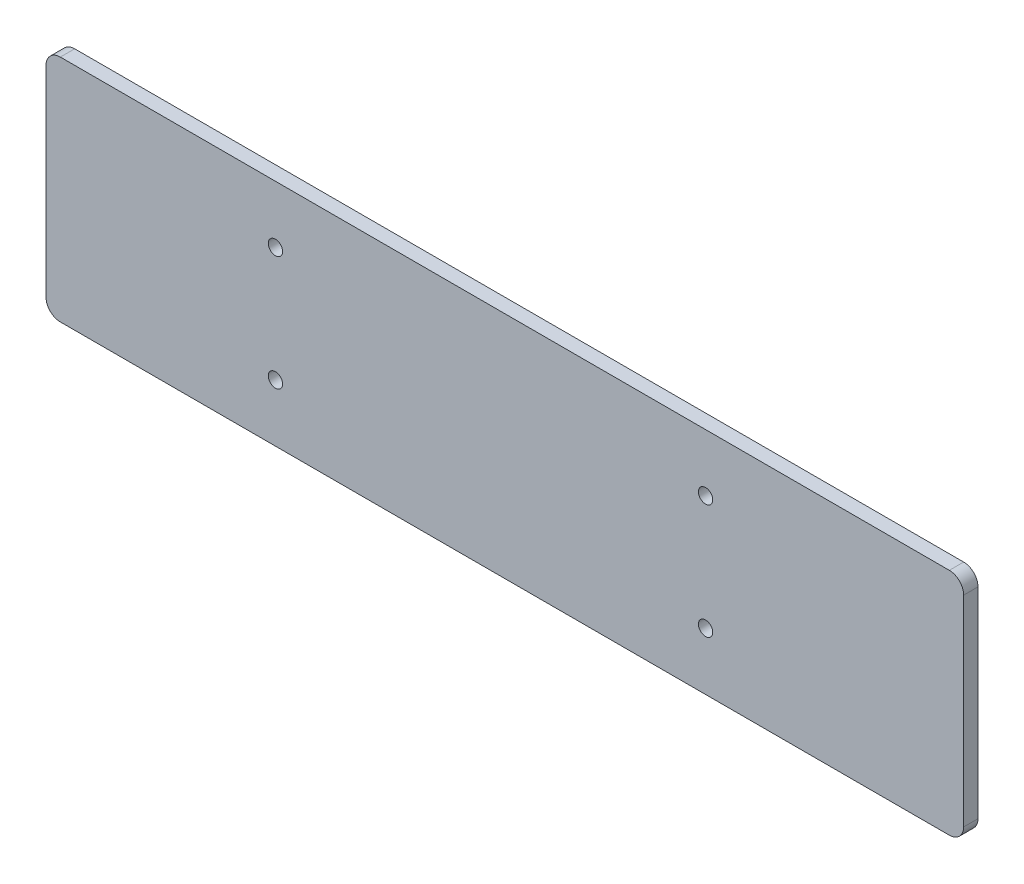
SolidWorks part; units mm, degrees
ref_plane "Front Plane" through (0, 0, 0) normal (0, 0, 1) x (1, 0, 0)
ref_plane "Top Plane" through (0, 0, 0) normal (0, 1, 0) x (1, 0, 0)
ref_plane "Right Plane" through (0, 0, 0) normal (1, 0, 0) x (0, 0, -1)
sketch "Sketch1" plane through (0, 0, 0) normal (0, 0, 1) x (1, 0, 0)
  line L0 (110, -40) -> (-210, -40)
  line L1 (110, -40) -> (110, 40)
  line L2 (110, 40) -> (-210, 40)
  line L3 (-210, -40) -> (-210, 40)
  line L4 (110, -40) -> (-210, 40) construction
  line L5 (110, 40) -> (-210, -40) construction
  circle A0 centre (-130, -20) radius 2.5
  circle A1 centre (-130, 20) radius 2.5
  circle A2 centre (20, 20) radius 2.5
  circle A3 centre (20, -20) radius 2.5
  point P0 (-50, 0)
  dimension "D3" = 5
  dimension "D4" = 5
  dimension "D8" = 5
  dimension "D9" = 5
  dimension "D11" = 150
  dimension "D1" = 320
  dimension "D2" = 80
  dimension "D5" = 80
  dimension "D6" = 60
  dimension "D7" = 20
extrude "Boss-Extrude1" add sketch "Sketch1" along normal blind 5
fillet "Fillet1" radius 5 4 edges at (-210, -40, 2.5) (-210, 40, 2.5) (110, -40, 2.5) (110, 40, 2.5)
